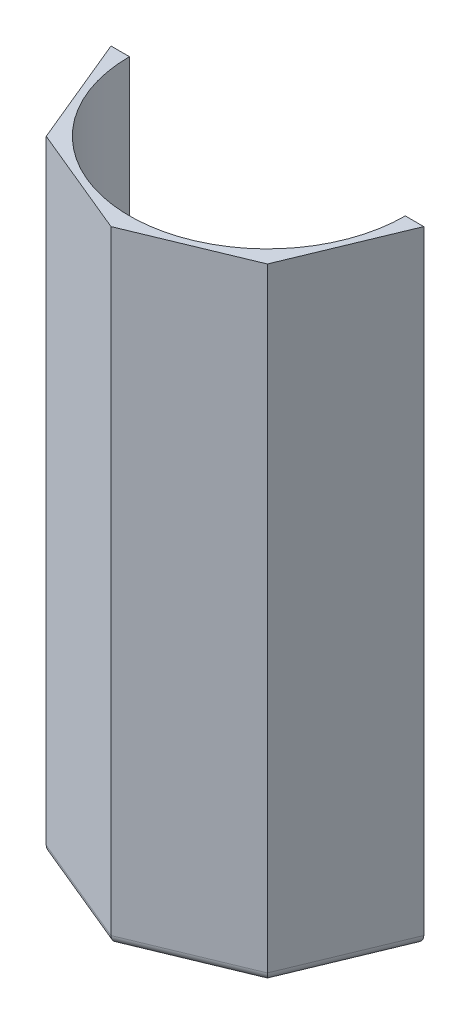
SolidWorks part; units mm, degrees
ref_plane "Front Plane" through (0, 0, 0) normal (0, 0, 1) x (1, 0, 0)
ref_plane "Top Plane" through (0, 0, 0) normal (0, 1, 0) x (1, 0, 0)
ref_plane "Right Plane" through (0, 0, 0) normal (1, 0, 0) x (0, 0, -1)
sketch "Sketch1" plane through (0, 0, 0) normal (0, 1, 0) x (1, 0, 0)
  line L1 (35.15, 0) -> (24.8548, 24.8548)
  line L2 (24.8548, 24.8548) -> (0, 35.15)
  line L3 (0, 35.15) -> (-24.8548, 24.8548)
  line L4 (-24.8548, 24.8548) -> (-35.15, 0)
  line L5 (-35.15, 0) -> (-24.8548, -24.8548)
  line L6 (-24.8548, -24.8548) -> (0, -35.15)
  line L7 (0, -35.15) -> (24.8548, -24.8548)
  line L8 (24.8548, -24.8548) -> (35.15, 0)
  circle A0 centre (0, 0) radius 32.4744 construction
  dimension "D1" = 35.15
extrude "Boss-Extrude1" add sketch "Sketch1" along normal blind 140
sketch "Sketch2" plane through (0, 140, 0) normal (0, 1, 0) x (1, 0, 0)
  circle A0 centre (0, 0) radius 31
extrude "Cut-Extrude1" cut sketch "Sketch2" against normal blind 133.5 contours A0
sketch "Sketch3" plane through (0, 0, 0) normal (0, -1, 0) x (-1, 0, 0)
  circle A0 centre (0, 0) radius 26
extrude "Cut-Extrude2" cut sketch "Sketch3" against normal blind 133.5
fillet "Fillet1" radius 2 8 edges at (12.4274, 0, 30.0024) (30.0024, 0, 12.4274) (30.0024, 0, -12.4274) (12.4274, 0, -30.0024) (-12.4274, 0, -30.0024) (-30.0024, 0, -12.4274) (-12.4274, 0, 30.0024) (-30.0024, 0, 12.4274)
sketch "Sketch4" plane through (0, 140, 0) normal (0, 1, 0) x (1, 0, 0)
  line L0 (-35.15, 0) -> (35.15, 0)
  line L1 (35.15, 0) -> (24.8548, 24.8548)
  line L2 (24.8548, 24.8548) -> (0, 35.15)
  line L3 (0, 35.15) -> (-24.8548, 24.8548)
  line L4 (-24.8548, 24.8548) -> (-35.15, 0)
extrude "Cut-Extrude3" cut sketch "Sketch4" against normal blind 173.5
